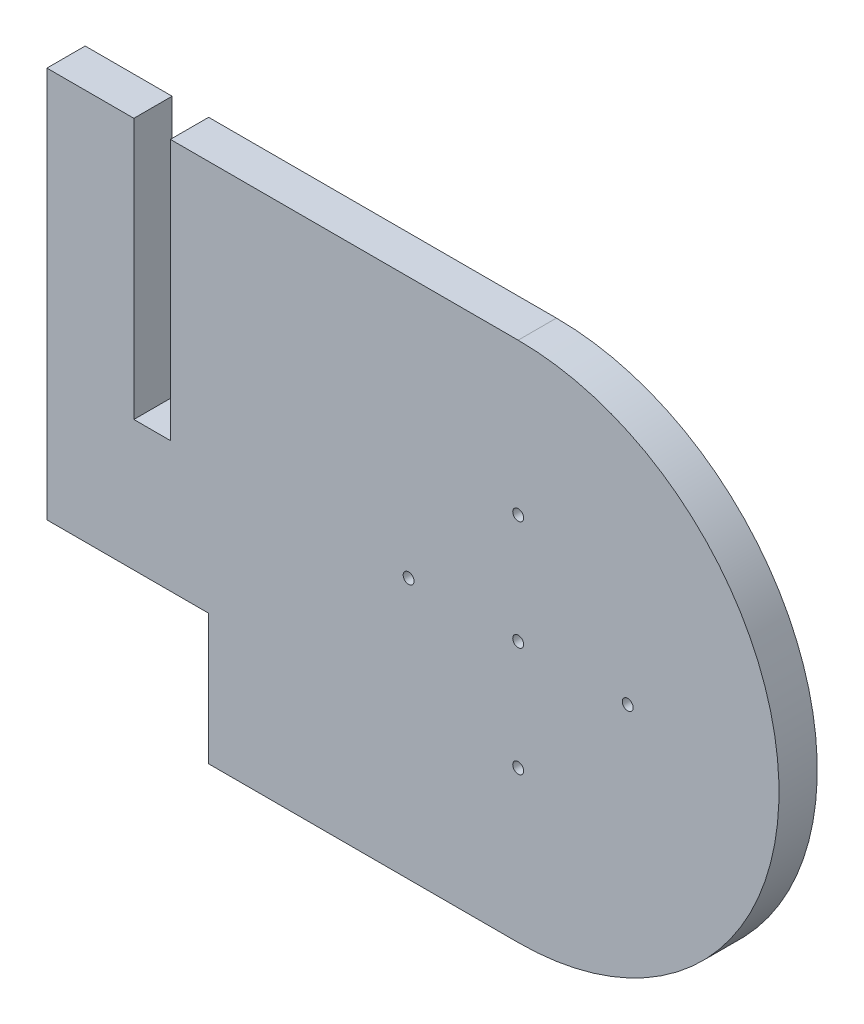
SolidWorks part; units mm, degrees
ref_plane "Front Plane" through (0, 0, 0) normal (0, 0, 1) x (1, 0, 0)
ref_plane "Top Plane" through (0, 0, 0) normal (0, 1, 0) x (1, 0, 0)
ref_plane "Right Plane" through (0, 0, 0) normal (1, 0, 0) x (0, 0, -1)
sketch "Sketch1" plane through (0, 0, 0) normal (0, 0, 1) x (1, 0, 0)
  line L0 (-6.7281, 19.05) -> (18.6719, 19.05)
  line L1 (-3.9341, -19.05) -> (18.6719, -19.05)
  line L2 (-15.7451, -9.525) -> (-15.7451, 19.05)
  line L3 (-15.7451, 19.05) -> (-9.3951, 19.05)
  line L5 (-3.9341, -9.525) -> (-15.7451, -9.525)
  line L6 (-15.7451, 19.05) -> (0, 0) construction
  line L7 (-3.9341, -9.525) -> (-3.9341, -19.05)
  line L8 (-9.3951, 19.05) -> (-9.3951, 0)
  line L9 (-9.3951, 0) -> (-6.7281, 0)
  line L10 (-6.7281, 19.05) -> (-6.7281, 0)
  arc A0 (18.6719, -19.05) -> (18.6719, 19.05) centre (18.6719, 0) ccw
  circle A1 centre (18.6719, 8) radius 0.3969
  circle A2 centre (18.6719, 0) radius 0.3969
  circle A3 centre (26.6719, 0) radius 0.3969
  circle A4 centre (18.6719, -8) radius 0.3969
  circle A5 centre (10.6719, 0) radius 0.3969
  point P0 (0, 0)
  point P24 (18.6719, 0)
  dimension "D2" = 0.7937
  dimension "D6" = 0.7937
  dimension "D1" = 25.4
  dimension "D3" = 2.667
  dimension "D4" = 6.35
  dimension "D5" = 8
  dimension "D8" = 9.525
  dimension "D9" = 2.794
  dimension "D7" = 4
extrude "Boss-Extrude1" add sketch "Sketch1" along normal blind 2.794
